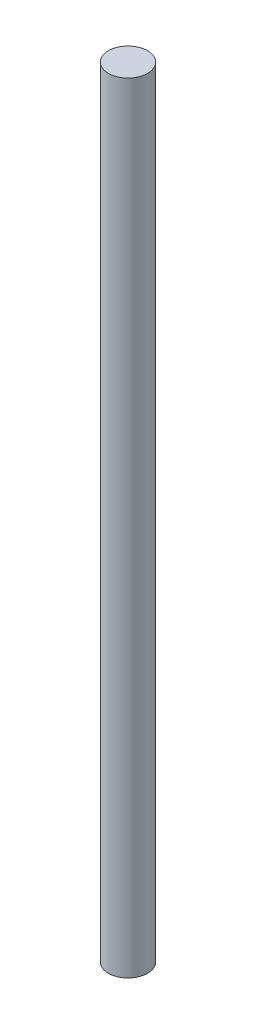
SolidWorks part; units mm, degrees
ref_plane "前视基准面" through (0, 0, 0) normal (0, 0, 1) x (1, 0, 0)
ref_plane "上视基准面" through (0, 0, 0) normal (0, 1, 0) x (1, 0, 0)
ref_plane "右视基准面" through (0, 0, 0) normal (1, 0, 0) x (0, 0, -1)
sketch "草图1" plane through (0, 0, 0) normal (0, 1, 0) x (1, 0, 0)
  circle A0 centre (0, 0) radius 2.015
  dimension "D1" = 4.03
extrude "凸台-拉伸1" add sketch "草图1" along normal blind 80
cosmetic thread "装饰螺纹线1" parameters "D1"=20, "D2"=3.242
